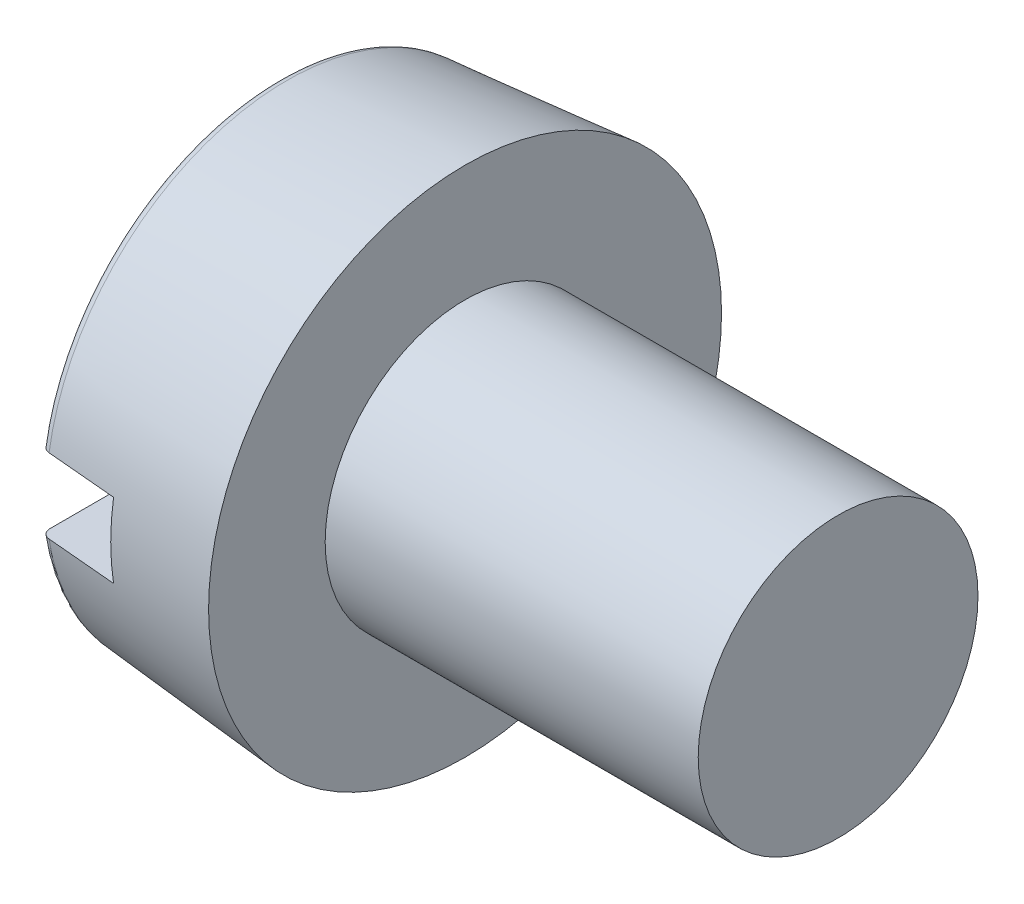
SolidWorks part; units mm, degrees
material "PA Type 6"
ref_plane "Plane1" through (0, 0, 0) normal (0, 0, 1) x (1, 0, 0)
ref_plane "Plane2" through (0, 0, 0) normal (0, 1, 0) x (1, 0, 0)
ref_plane "Plane3" through (0, 0, 0) normal (1, 0, 0) x (0, 0, -1)
sketch "BodySke" plane through (0, 0, 0) normal (0, 0, 1) x (1, 0, 0)
  line L0 (2, 1.5) -> (2, 2.75)
  line L1 (0, 0) -> (0, 2.575)
  line L2 (-25.4, 0) -> (127, 0) construction
  line L3 (6, 0) -> (0, 0)
  line L4 (2, 1.5) -> (6, 1.5)
  line L5 (6, 1.5) -> (6, 0)
  line L6 (0, 2.575) -> (2, 2.75)
  line L9 (2.5, 3.0875) -> (2.5, -6.4375) construction
  line L10 (2, 6.35) -> (2, -3.175) construction
  dimension "Length" = 4
  dimension "Head_ht" = 2
  dimension "Advance" = 0.5
  dimension "Thread_nom" = 4
  dimension "Head_dia" = 5.5
  dimension "Head_side_angle" = 5
  dimension "Diameter" = 3
revolve "Base-Revolve" add sketch "BodySke"
cosmetic thread "ThreadCosmetic" [suppressed]
fillet "Fillet1" [suppressed] radius 0.1
fillet "Fillet2" radius 0.1 1 edges at (0, 0, 2.575)
sketch "Sketch2" plane through (0, 0, 0) normal (1, 0, 0) x (0, 0, -1)
  line L0 (2.75, -0.4) -> (-2.75, -0.4)
  line L1 (2.75, -0.4) -> (2.75, 0.4)
  line L2 (-2.75, 0.4) -> (2.75, 0.4)
  line L3 (-2.75, 0.4) -> (-2.75, -0.4)
  dimension "D1" = 5.5
  dimension "Slot_width" = 0.8
  dimension "D2" = 2.75
  dimension "D3" = 0.4
extrude "Slot" cut sketch "Sketch2" along normal blind 0.85
sketch "ThdSchSke" plane through (0, 0, 0) normal (0, 0, 1) x (1, 0, 0)
  line L0 (3, -1.2195) -> (2.8036, -1.5)
  line L1 (3, -1.2195) -> (3.1964, -1.5)
  line L2 (3.1964, -1.5) -> (3.1964, -1.875)
  line L3 (-3.175, 0) -> (5.1513, 0) construction
  line L5 (3.1964, -1.875) -> (2.8036, -1.875)
  line L6 (2.8036, -1.875) -> (2.8036, -1.5)
  dimension "Diameter" = 3
  dimension "SideAngle" = 55
  dimension "VeeAngle" = 70
  dimension "Thread_minor" = 2.439
  dimension "Overcut" = 3.75
  dimension "Start" = 3
revolve "ThreadSchematic" [suppressed] cut sketch "ThdSchSke" angle 360 about L3
pattern_linear "ThdSchPat" [suppressed]
equation "\"D1@Sketch2\" = \"Head_dia@BodySke\""
equation "\"D2@Sketch2\" = \"D1@Sketch2\" / 2"
equation "\"D3@Sketch2\" = \"Slot_width@Sketch2\" / 2"
equation "\"Thread_length@ThreadCosmetic\" = ((sgn( (\"Length@BodySke\" - \"Advance@BodySke\" * 2.0 ) - \"Thread_nom@BodySke\" )-1)*( (\"Length@BodySke\" - \"Advance@BodySke\"  * 2.0) - \"Thread_nom@BodySke\" ))/-2+ \"Thread_nom@BodySke\""
equation "\"Thread_minor@ThdSchSke\" = \"Thread_minor@ThreadCosmetic\""
equation "\"Diameter@ThdSchSke\" = \"Diameter@BodySke\""
equation "\"Overcut@ThdSchSke\" = \"Diameter@BodySke\" * 1.25"
equation "\"Start@ThdSchSke\" = \"Head_ht@BodySke\" + \"Length@BodySke\" - \"Thread_length@ThreadCosmetic\"  '---Non-countersunk---"
equation "\"Num_threads@ThdSchPat\" = int( \"Thread_length@ThreadCosmetic\" / \"Advance@BodySke\" + 0.999 )  + 1"
equation "\"Advance@ThdSchPat\" = \"Thread_length@ThreadCosmetic\" /  (\"Num_threads@ThdSchPat\" - 1) 'relax it"
